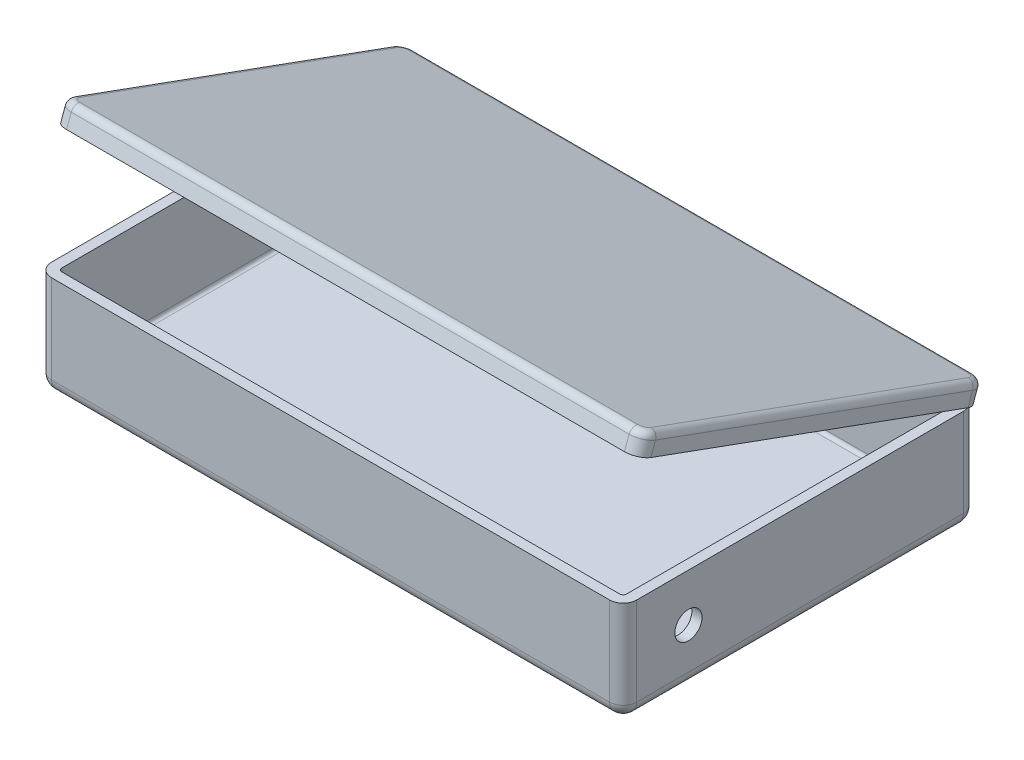
SolidWorks part; units mm, degrees
material "Acrylic (Medium-high impact)"
ref_plane "Front" through (0, 0, 0) normal (0, 0, 1) x (1, 0, 0)
ref_plane "Top" through (0, 0, 0) normal (0, 1, 0) x (1, 0, 0)
ref_plane "Right" through (0, 0, 0) normal (1, 0, 0) x (0, 0, -1)
sketch "Sketch1" plane through (0, 0, 0) normal (0, 1, 0) x (1, 0, 0)
  line L1 (-136.525, 82.55) -> (136.525, 82.55)
  line L2 (-136.525, 82.55) -> (-136.525, -82.55)
  line L3 (-136.525, -82.55) -> (136.525, -82.55)
  line L4 (136.525, 82.55) -> (136.525, -82.55)
  line L5 (-136.525, 82.55) -> (136.525, -82.55) construction
  line L6 (-136.525, -82.55) -> (136.525, 82.55) construction
  point P0 (0, 0)
  dimension "D1" = 273.05
  dimension "D2" = 165.1
extrude "Boss-Extrude1" add sketch "Sketch1" along normal blind 47.625
fillet "Fillet1" radius 6.35 8 edges at (0, 0, -82.55) (-136.525, 0, 0) (0, 0, 82.55) (136.525, 0, 0) (-136.525, 23.8125, -82.55) (136.525, 23.8125, -82.55) (136.525, 23.8125, 82.55) (-136.525, 23.8125, 82.55)
shell "Shell1" thickness 4.7625
sketch "Sketch2" plane through (0, 0, 0) normal (1, 0, 0) x (0, 0, -1)
  line L0 (82.55, 47.625) -> (84.3461, 45.8289) construction
  line L2 (84.3461, 45.8289) -> (-75.5708, 104.0339)
  line L3 (-75.5708, 104.0339) -> (-72.3131, 112.9845)
  line L4 (-72.3131, 112.9845) -> (87.6038, 54.7795)
  line L5 (84.3461, 45.8289) -> (87.6038, 54.7795)
  line L6 (82.55, 47.625) -> (82.55, 45.8289) construction
  line L7 (82.55, 45.8289) -> (84.3461, 45.8289) construction
  line L8 (-76.2, 47.625) -> (76.2, 47.625) construction
  dimension "D1" = 2.54
  dimension "D2" = 9.525
  dimension "D3" = 170.18
  dimension "D4" = 20
extrude "LID OPENING ANGLE CONTROL" add sketch "Sketch2" along normal mid plane 273.05 separate body
fillet "Fillet2" radius 6.35 4 edges at (136.525, 50.3042, -85.9749) (-136.525, 50.3042, -85.9749) (136.525, 108.5092, 73.942) (-136.525, 108.5092, 73.942)
fillet "Fillet3" radius 3.175 8 edges at (134.6651, 112.3484, 70.5654) (0, 112.9845, 72.3131) (-134.6651, 112.3484, 70.5654) (-136.525, 83.882, -7.6453) (-134.6651, 55.4156, -85.8561) (0, 54.7795, -87.6038) (134.6651, 55.4156, -85.8561) (136.525, 83.882, -7.6453)
shell "Shell2" thickness 2.54
sketch "Sketch3" plane through (136.525, 0, 0) normal (1, 0, 0) x (0, 0, -1)
  line L0 (76.2, 0) -> (-76.2, 0) construction
  line L1 (-82.55, 6.35) -> (-82.55, 47.625) construction
  circle A0 centre (-52.07, 25.4) radius 6.35
  dimension "D1" = 12.7
  dimension "D2" = 25.4
  dimension "D3" = 30.48
extrude "Cut-Extrude1" cut sketch "Sketch3" against normal up to next (4.7625 mm away)
